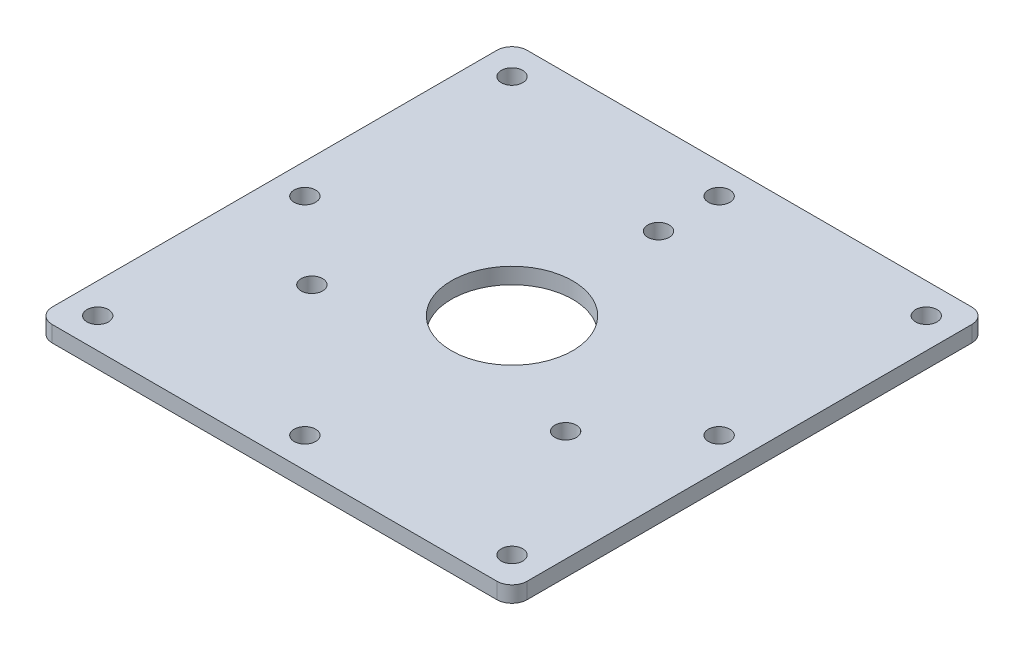
SolidWorks part; units mm, degrees
ref_plane "Front Plane" through (0, 0, 0) normal (0, 0, 1) x (1, 0, 0)
ref_plane "Top Plane" through (0, 0, 0) normal (0, 1, 0) x (1, 0, 0)
ref_plane "Right Plane" through (0, 0, 0) normal (1, 0, 0) x (0, 0, -1)
sketch "Sketch1" plane through (0, 0, 0) normal (0, 1, 0) x (1, 0, 0)
  line L0 (-47, 0) -> (47, 0) construction
  line L1 (-47, -47) -> (47, -47)
  line L2 (-47, -47) -> (-47, 47)
  line L3 (-47, 47) -> (47, 47)
  line L4 (47, -47) -> (47, 47)
  line L5 (-47, -47) -> (47, 47) construction
  line L6 (-47, 47) -> (47, -47) construction
  line L7 (0, 47) -> (0, -47) construction
  circle A0 centre (0, 0) radius 12
  circle A1 centre (0, 29) radius 2.125
  circle A2 centre (25.1147, -14.5) radius 2.125
  circle A3 centre (-25.1147, -14.5) radius 2.125
  circle A4 centre (-41, -41) radius 2.125
  circle A5 centre (-41, 0) radius 2.125
  circle A6 centre (-41, 41) radius 2.125
  circle A7 centre (41, -41) radius 2.125
  circle A8 centre (41, 0) radius 2.125
  circle A9 centre (41, 41) radius 2.125
  circle A10 centre (0, -41) radius 2.125
  circle A11 centre (0, 41) radius 2.125
  circle A12 centre (0, 0.554) radius 35 construction
  point P0 (0, 0)
  point P16 (0, 0)
  dimension "D1" = 24
  dimension "D2" = 4.25
  dimension "D7" = 4.25
  dimension "D10" = 4.25
  dimension "D11" = 4.25
  dimension "D13" = 70
  dimension "D3" = 29
  dimension "D5" = 94
  dimension "D6" = 94
  dimension "D8" = 6
  dimension "D9" = 6
  dimension "D12" = 6
  dimension "D14" = 6
  dimension "D4" = 3
extrude "Boss-Extrude1" add sketch "Sketch1" along normal blind 3.175
fillet "Fillet1" radius 3 4 edges at (-47, 1.5875, -47) (47, 1.5875, 47) (47, 1.5875, -47) (-47, 1.5875, 47)
